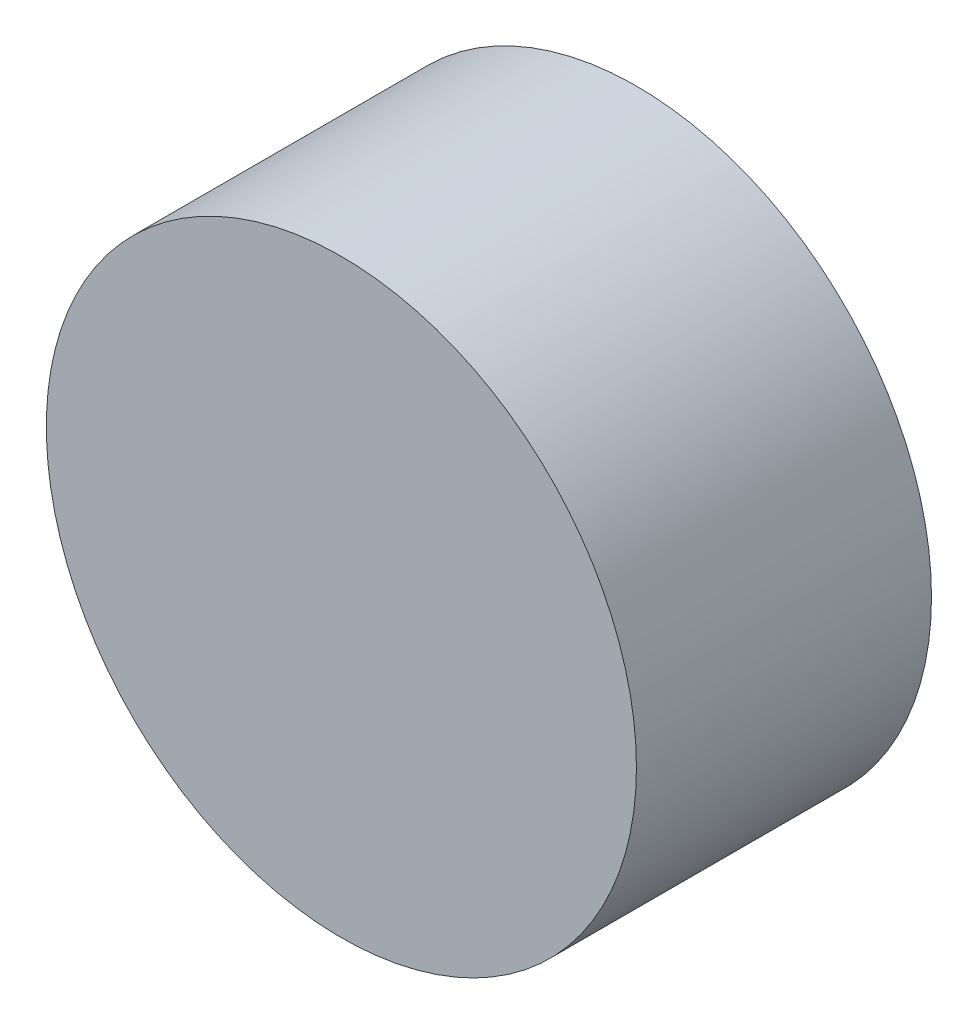
SolidWorks part; units mm, degrees
ref_plane "Front Plane" through (0, 0, 0) normal (0, 0, 1) x (1, 0, 0)
ref_plane "Top Plane" through (0, 0, 0) normal (0, 1, 0) x (1, 0, 0)
ref_plane "Right Plane" through (0, 0, 0) normal (1, 0, 0) x (0, 0, -1)
sketch "ｽｹｯﾁ1" plane through (0, 0, 0) normal (0, 0, 1) x (1, 0, 0)
  circle A0 centre (0, 0) radius 3
  dimension "D1" = 6
extrude "ﾎﾞｽ - 押し出し1" add sketch "ｽｹｯﾁ1" along normal blind 3
